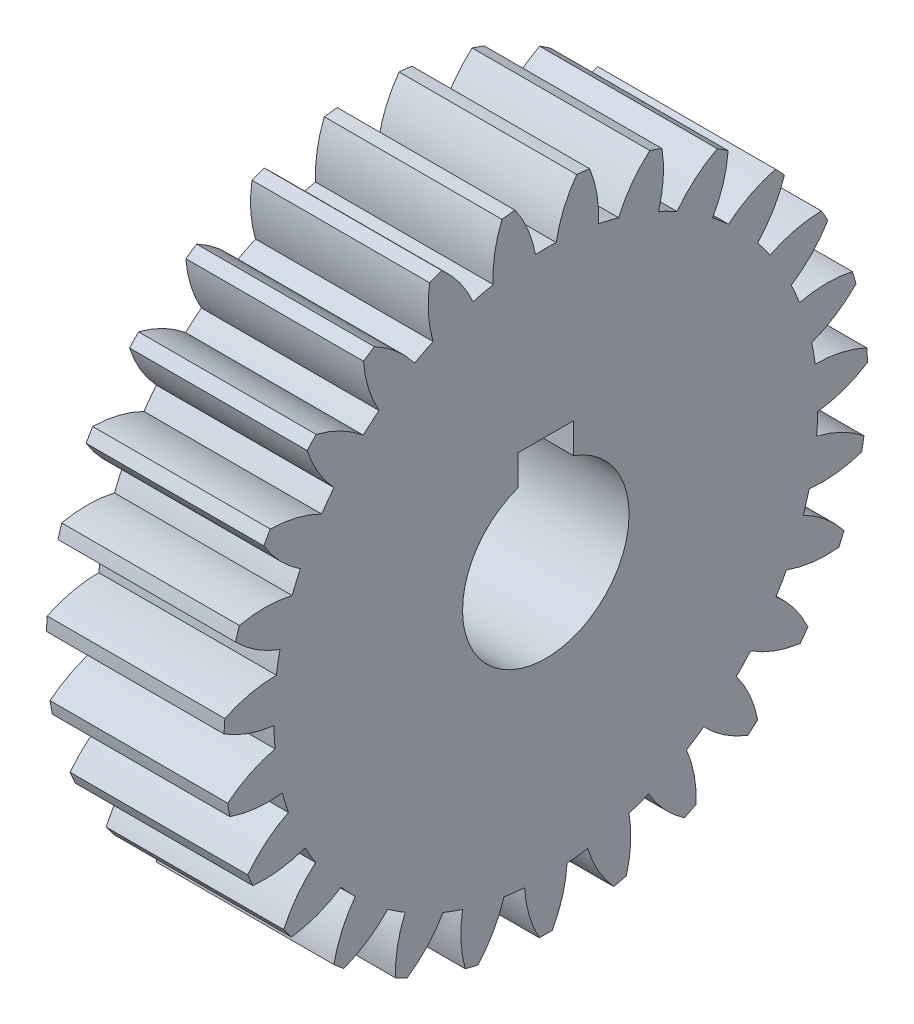
SolidWorks part; units mm, degrees
ref_plane "Plane1" through (0, 0, 0) normal (0, 0, 1) x (1, 0, 0)
ref_plane "Plane2" through (0, 0, 0) normal (0, 1, 0) x (1, 0, 0)
ref_plane "Plane3" through (0, 0, 0) normal (1, 0, 0) x (0, 0, -1)
sketch "HoldingSke" plane through (0, 0, 0) normal (0, 1, 0) x (1, 0, 0)
  line L0 (0, 0) -> (0.4455, -0.227)
  line L1 (-15, 0) -> (100, 0) construction
  line L2 (0, 0) -> (-2.1039, 2.3779)
  line L3 (0, 0) -> (-11.863, 4.5341)
  line L4 (0, 0) -> (7.6947, 3.9207)
  line L5 (0, 0) -> (-46.8476, -17.4728)
  line L6 (0, 0) -> (-13.2634, -8.9489)
  line L7 (-2.1039, 2.3779) -> (8.6586, 51.2059)
  line L8 (-76.2, 54.61) -> (-73.9, 54.61)
  line L9 (-71.009, 38.7566) -> (-53.1078, 45.2721)
  line L10 (-76.2, 71.12) -> (104.1128, 71.12)
  line L11 (0, 0) -> (-16, 0)
  line L12 (-76.2, 101.6) -> (-76.133, 101.6)
  line L13 (24.9733, 27.94) -> (52.9518, 28.4284)
  line L14 (24.9733, 27.94) -> (24.9743, 27.94)
  line L15 (24.9733, 27.94) -> (100.4006, 29.5858)
  line L16 (-63.627, -2) -> (-12.827, -2)
  circle A0 centre (0, 0) radius 7.5
  circle A1 centre (0, 0) radius 24.499
  circle A2 centre (0, 0) radius 37.5
  circle A3 centre (0, 0) radius 7.5
  dimension "MHD" = 48.998
  dimension "Hub_dia" = 75
  dimension "Bore" = 15
  dimension "MBD" = 15
  dimension "Num_teeth" = 27
  dimension "Pitch" = 0.5
  dimension "Overall_len" = 50
  dimension "Show_teeth" = 27
  dimension "Thickness" = 16
  dimension "OAL" = 50.0001
  dimension "T_dim" = 2.3
  dimension "Ap" = 20
  dimension "H" = 19.05
  dimension "Pitch_radius" = 180.3128
  dimension "Width" = 16
  dimension "Backlash" = 0.067
  dimension "Addendum_fac" = 1
  dimension "Dedendum_fac" = 1.25
  dimension "Clearance_fac" = 0.25
  dimension "Dedendum_add" = 0.001
  dimension "Module" = 2
sketch "BasProSke" plane through (0, 0, 0) normal (0, 1, 0) x (1, 0, 0)
  line L0 (-10, 0) -> (60, 0) construction
  line L1 (0, 0) -> (0, 29)
  line L2 (0, 0) -> (16, 0)
  line L3 (16, 0) -> (16, 29)
  line L4 (16, 29) -> (0, 29)
  dimension "Thickness" = 16
  dimension "Diameter" = 58
revolve "Base-Revolve" add sketch "BasProSke" angle 360 about L0
sketch "TooCutSke" plane through (0, 0, 0) normal (1, 0, 0) x (0, 0, -1)
  line L1 (0, 0) -> (0, 107) construction
  line L2 (0, 0) -> (-1.6871, 26.9472) construction
  line L3 (0, 0) -> (-6.2599, 53.5572) construction
  line L4 (-1.6871, 26.9472) -> (-3.13, 26.7786) construction
  arc A0 (0.934, 24.4812) -> (-0.934, 24.4812) centre (0, 0) ccw
  arc A1 (2.7993, 28.8901) -> (-2.7993, 28.8901) centre (0, 0) ccw
  circle A2 centre (0, 0) radius 27 construction
  circle A3 centre (0, 0) radius 25.3717 construction
  arc A4 (-0.934, 24.4812) -> (-2.7993, 28.8901) centre (-11.5657, 22.5822) ccw
  arc A5 (2.7993, 28.8901) -> (0.934, 24.4812) centre (11.5657, 22.5822) ccw
  dimension "Root_dia" = 48.998
  dimension "Overcut_dia" = 58.0508
  dimension "Pitch_dia" = 54
  dimension "Base_dia" = 50.7434
  dimension "Flank_rad" = 10.8
  dimension "Half_ang" = 6.667
  dimension "Half_CT" = 1.4527
extrude "ToothCut" cut sketch "TooCutSke" along normal through all
fillet "Breaks" [suppressed] radius 0.04
fillet "RootFillets" [suppressed] radius 0.501
pattern_circular "TeethCuts" count 27 every 13.333 about axis through (-10, 0, 0) along (1, 0, 0) of "ToothCut", "RootFillets", "Breaks"
sketch "HubNeaOneSke" plane through (0, 0, 0) normal (-1, 0, 0) x (0, 0, 1)
  circle A0 centre (0, 0) radius 24.499
  dimension "Diameter" = 48.998
extrude "HubNearOne" [suppressed] add sketch "HubNeaOneSke" along normal blind 34.0001
sketch "HubNeaBotSke" plane through (0, 0, 0) normal (-1, 0, 0) x (0, 0, 1)
  circle A0 centre (0, 0) radius 24.499
  dimension "Diameter" = 48.998
extrude "HubNearBoth" [suppressed] add sketch "HubNeaBotSke" along normal blind 17
ref_plane "FarPln" through (16, 0, 0) normal (1, 0, 0) x (0, 0, -1)
sketch "HubFarSke" plane through (16, 0, 0) normal (1, 0, 0) x (0, 0, -1)
  circle A0 centre (0, 0) radius 24.499
  dimension "Diameter" = 48.998
extrude "HubFar" [suppressed] add sketch "HubFarSke" along normal blind 17
sketch "BorSke" plane through (0, 0, 0) normal (1, 0, 0) x (0, 0, -1)
  circle A0 centre (0, 0) radius 7.5
  dimension "Diameter" = 15
extrude "Bore" cut sketch "BorSke" along normal mid plane 100.0001
sketch "KeySke" plane through (0, 0, 0) normal (1, 0, 0) x (0, 0, -1)
  line L0 (-2.5, 0) -> (-2.5, 9.8)
  line L1 (-2.5, 9.8) -> (2.5, 9.8)
  line L2 (2.5, 9.8) -> (2.5, 0)
  line L3 (0, 0) -> (0, 34) construction
  line L4 (-2.5, 0) -> (2.5, 0)
  dimension "Offset" = 9.8
  dimension "Width" = 5
extrude "Keyway" cut sketch "KeySke" along normal mid plane 100.0001
pattern_circular "Keyway2" [suppressed] count 2 every 90 about axis through (-10, 0, 0) along (1, 0, 0)
equation "' \"Module@HoldingSke\" = 6.35"
equation "' \"Num_teeth@HoldingSke\" = 12"
equation "' \"Ap@HoldingSke\" =  20"
equation "' \"Ap@HoldingSke\" = 20"
equation "' \"Width@HoldingSke\" = 0.5 * 25.4"
equation "' \"Hub_dia@HoldingSke\"= 1 * 25.4"
equation "' \"Hub_dia@HoldingSke\" = 1 * 25.4"
equation "' \"Overall_len@HoldingSke\" = 1.0 * 25.4"
equation "' \"Bore@HoldingSke\" = 0.75 * 25.4"
equation "' \"T_dim@HoldingSke\" = 0.1 * 25.4"
equation "' \"Width@KeySke\" = 0.25 * 25.4"
equation "' \"Show_teeth@HoldingSke\" = 13"
equation "' \"Backlash@HoldingSke\" = 0.009 * 25.4"
equation "' \"Addendum_fac@HoldingSke\" = 1.0"
equation "' \"Dedendum_fac@HoldingSke\" = 1.25"
equation "' \"Dedendum_add@HoldingSke\" = 0.00005 * 25.4"
equation "' \"Clearance_fac@HoldingSke\" = 0.25"
equation "\"Pitch@HoldingSke\" = 1 / \"Module@HoldingSke\""
equation "\"Overcut_dia@TooCutSke\" = (\"Num_teeth@HoldingSke\" + 2 * \"Addendum_fac@HoldingSke\") / \"Pitch@HoldingSke\" + 0.002 * 25.4"
equation "\"Pitch_dia@TooCutSke\" = \"Num_teeth@HoldingSke\" / \"Pitch@HoldingSke\""
equation "\"Base_dia@TooCutSke\" = \"Num_teeth@HoldingSke\" / \"Pitch@HoldingSke\" * cos((\"Ap@HoldingSke\"  * 3.14159265 / 180))"
equation "\"Root_dia@TooCutSke\" = (\"Num_teeth@HoldingSke\" + 2) / \"Pitch@HoldingSke\" - 2 * (\"Addendum_fac@HoldingSke\" + \"Dedendum_fac@HoldingSke\") / \"Pitch@HoldingSke\" - \"Dedendum_add@HoldingSke\" * 2"
equation "\"Half_ang@TooCutSke\" = 180 / \"Num_teeth@HoldingSke\""
equation "\"Half_CT@TooCutSke\" = \"Num_teeth@HoldingSke\" / \"Pitch@HoldingSke\" * sin((3.14159265 / 2 / \"Num_teeth@HoldingSke\")) / 2 - 7 * \"Backlash@HoldingSke\" / 4"
equation "\"Flank_rad@TooCutSke\" = \"Num_teeth@HoldingSke\" / \"Pitch@HoldingSke\" / 5"
equation "\"Radius@RootFillets\" = \"Clearance_fac@HoldingSke\" / \"Pitch@HoldingSke\" + \"Dedendum_add@HoldingSke\""
equation "\"Break_rad@Breaks\" = 0.02 / \"Pitch@HoldingSke\""
equation "\"Thickness@HoldingSke\" = \"Width@HoldingSke\""
equation "\"OAL@HoldingSke\" = \"Thickness@HoldingSke\""
equation "\"MHD@HoldingSke\" = (\"Num_teeth@HoldingSke\" + 2) / \"Pitch@HoldingSke\" - 2 * (\"Addendum_fac@HoldingSke\" + \"Dedendum_fac@HoldingSke\")  / \"Pitch@HoldingSke\" - \"Dedendum_add@HoldingSke\" * 2"
equation "\"MBD@HoldingSke\" = (\"Num_teeth@HoldingSke\" + 2) / \"Pitch@HoldingSke\" - 2 * (\"Addendum_fac@HoldingSke\" + \"Dedendum_fac@HoldingSke\")  / \"Pitch@HoldingSke\" - \"Dedendum_add@HoldingSke\" * 2 - 0.002 * 25.4"
equation "\"MHD@HoldingSke\" = ((sgn( \"MHD@HoldingSke\" - \"Hub_dia@HoldingSke\" )-1)*( \"MHD@HoldingSke\" - \"Hub_dia@HoldingSke\" ))/-2+ \"Hub_dia@HoldingSke\""
equation "\"MBD@HoldingSke\" = ((sgn( \"MBD@HoldingSke\" - \"Bore@HoldingSke\" )-1)*( \"MBD@HoldingSke\" - \"Bore@HoldingSke\" ))/-2+ \"Bore@HoldingSke\""
equation "\"OAL@HoldingSke\" = ((sgn( \"OAL@HoldingSke\" - \"Overall_len@HoldingSke\" )+1)*( \"OAL@HoldingSke\" - \"Overall_len@HoldingSke\" ))/2 + \"Overall_len@HoldingSke\" + 0.000002 * 25.4"
equation "\"Num_teeth@TeethCuts\" = int( \"Show_teeth@HoldingSke\" ) + 1"
equation "\"Num_teeth@TeethCuts\" = ((sgn( \"Num_teeth@TeethCuts\" - \"Num_teeth@HoldingSke\" )-1)*( \"Num_teeth@TeethCuts\" - \"Num_teeth@HoldingSke\" ))/-2+ \"Num_teeth@HoldingSke\""
equation "\"Num_teeth@TeethCuts\" = ((sgn( \"Num_teeth@TeethCuts\" - 2.0)+1)*( \"Num_teeth@TeethCuts\" - 2.0))/2 +2.0"
equation "\"Angle@TeethCuts\" = 360.0 / \"Num_teeth@HoldingSke\""
equation "\"Diameter@BasProSke\" = (\"Num_teeth@HoldingSke\" + 2 * \"Addendum_fac@HoldingSke\") / \"Pitch@HoldingSke\""
equation "\"Thickness@BasProSke\"  = \"Thickness@HoldingSke\""
equation "' \"Fillet_rad@BasProSke\" =  \"Thickness@HoldingSke\" * 0.05"
equation "' \"Fillet_rad@BasProSke\" = \"Thickness@HoldingSke\" * 0.05"
equation "\"MHD@HoldingSke\" = ((sgn( \"MHD@HoldingSke\" - \"Root_dia@TooCutSke\" )-1)*( \"MHD@HoldingSke\" - \"Root_dia@TooCutSke\" ))/-2+ \"Root_dia@TooCutSke\""
equation "\"Diameter@HubNeaOneSke\" = \"MHD@HoldingSke\""
equation "\"Length@HubNearOne\" = \"OAL@HoldingSke\" - \"Thickness@BasProSke\""
equation "\"Diameter@HubNeaBotSke\" = \"MHD@HoldingSke\""
equation "\"Length@HubNearBoth\" = ( \"OAL@HoldingSke\" - \"Thickness@BasProSke\" ) / 2.0"
equation "\"Thickness@FarPln\" = \"Thickness@BasProSke\""
equation "\"Diameter@HubFarSke\" = \"MHD@HoldingSke\""
equation "\"Length@HubFar\" = ( \"OAL@HoldingSke\" - \"Thickness@BasProSke\" ) / 2.0"
equation "\"Diameter@BorSke\" = \"MBD@HoldingSke\""
equation "\"D1@Bore\" = \"OAL@HoldingSke\" * 2.0"
equation "\"D1@Keyway\" = \"OAL@HoldingSke\" * 2.0"
equation "\"Offset@KeySke\" = \"T_dim@HoldingSke\" + \"MBD@HoldingSke\" / 2.0"
